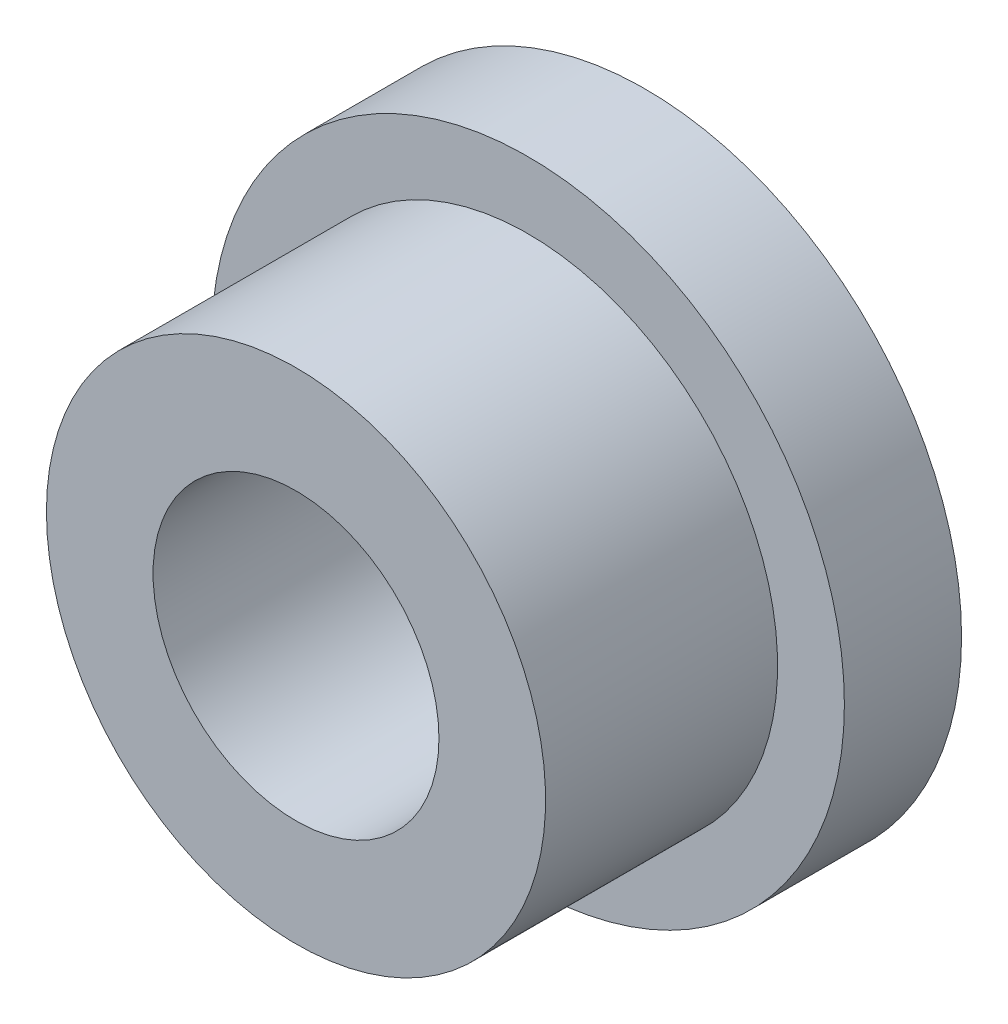
SolidWorks part; units mm, degrees
ref_plane "Front Plane" through (0, 0, 0) normal (0, 0, 1) x (1, 0, 0)
ref_plane "Top Plane" through (0, 0, 0) normal (0, 1, 0) x (1, 0, 0)
ref_plane "Right Plane" through (0, 0, 0) normal (1, 0, 0) x (0, 0, -1)
sketch "Sketch1" plane through (0, 0, 0) normal (0, 0, 1) x (1, 0, 0)
  circle A0 centre (0, 0) radius 13.5
extrude "Boss-Extrude1" add sketch "Sketch1" along normal blind 5
sketch "Sketch2" plane through (0, 0, 5) normal (0, 0, 1) x (1, 0, 0)
  circle A1 centre (0, 0) radius 10.65
sketch "Sketch5" plane through (0, 0, 5) normal (0, 0, 1) x (1, 0, 0)
  circle A0 centre (0, 0) radius 6.1
extrude "Boss-Extrude2" add sketch "Sketch2" along normal blind 9.9 contours A1
extrude "Cut-Extrude1" cut sketch "Sketch5" along normal blind 10 contours A0
